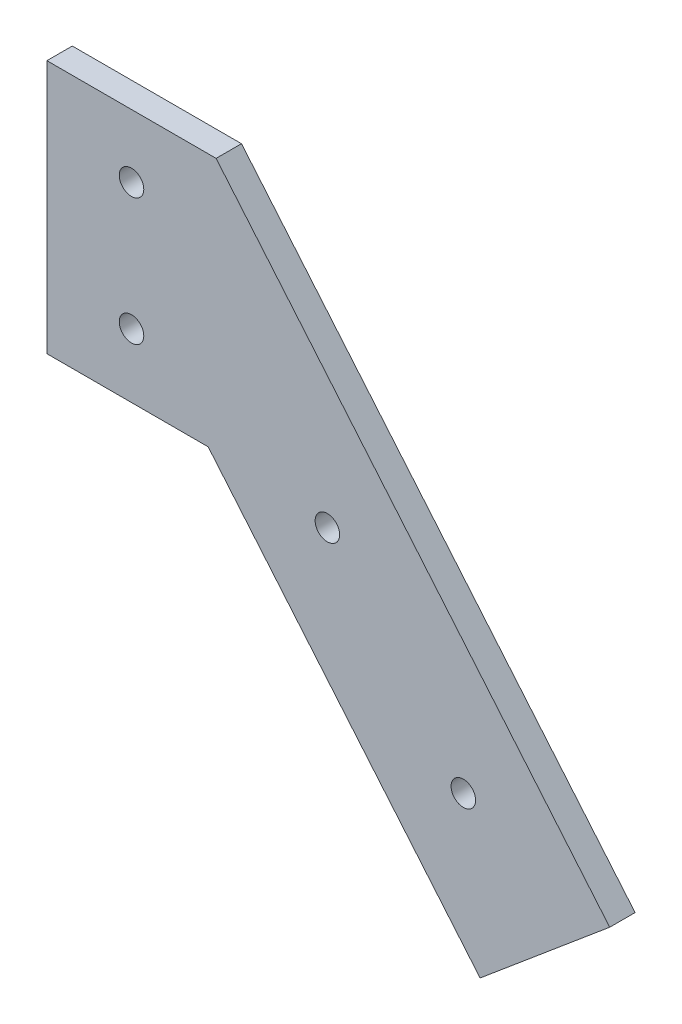
SolidWorks part; units mm, degrees
material "ABS"
ref_plane "Front Plane" through (0, 0, 0) normal (0, 0, 1) x (1, 0, 0)
ref_plane "Top Plane" through (0, 0, 0) normal (0, 1, 0) x (1, 0, 0)
ref_plane "Right Plane" through (0, 0, 0) normal (1, 0, 0) x (0, 0, -1)
sketch "Sketch1" plane through (0, 0, 0) normal (0, 0, 1) x (1, 0, 0)
  line L0 (20, 0) -> (66.5251, -55.4465)
  line L1 (0, 0) -> (20, 0)
  line L2 (0, 0) -> (0, -30)
  line L3 (0, -30) -> (19.0648, -30)
  line L5 (19.0648, -30) -> (51.2042, -68.3022)
  line L7 (51.2042, -68.3022) -> (66.5251, -55.4465)
  circle A0 centre (10, -7.4517) radius 1.45
  circle A1 centre (10, -22.4517) radius 1.45
  circle A2 centre (49.2229, -50.3837) radius 1.45
  circle A3 centre (33.1532, -31.2326) radius 1.45
  point P17 (10, 0)
  point P19 (58.8647, -61.8743)
  dimension "D3" = 2.9
  dimension "D1" = 20
  dimension "D2" = 230
  dimension "D4" = 30
  dimension "D5" = 20
  dimension "D6" = 50
  dimension "D7" = 15
  dimension "D8" = 15
  dimension "D9" = 25
extrude "Boss-Extrude1" add sketch "Sketch1" along normal blind 3
